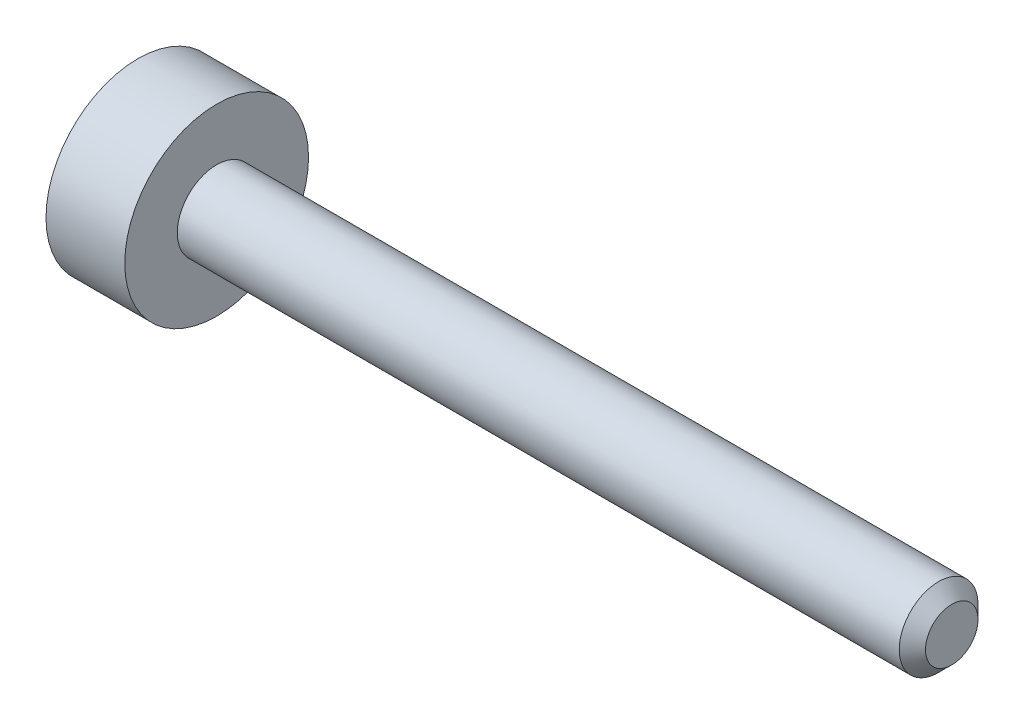
SolidWorks part; units mm, degrees
material "AISI 1020"
ref_plane "Front Plane" through (0, 0, 0) normal (0, 0, 1) x (1, 0, 0)
ref_plane "Top Plane" through (0, 0, 0) normal (0, 1, 0) x (1, 0, 0)
ref_plane "Right Plane" through (0, 0, 0) normal (1, 0, 0) x (0, 0, -1)
sketch "Sketch1" plane through (0, 0, 0) normal (0, 0, 1) x (1, 0, 0)
  line L0 (0, 0) -> (4.55, 0) construction
  line L1 (0, 0) -> (0, 1)
  line L2 (0, 1) -> (-0.5, 1.5)
  line L3 (-0.5, 1.5) -> (-28, 1.5)
  line L4 (-28, 1.5) -> (-28, 3.5)
  line L5 (-28, 3.5) -> (-31, 3.5)
  line L6 (-31, 3.5) -> (-31, 0)
  line L7 (-31, 0) -> (0, 0)
  dimension "D1" = 3
  dimension "D2" = 7
  dimension "D3" = 3
  dimension "D4" = 28
  dimension "D5" = 0.5
  dimension "D6" = 0.5
revolve "Revolve1" add sketch "Sketch1" angle 360 about L0
sketch "Sketch2" plane through (-31, 0, 0) normal (-1, 0, 0) x (0, 0, 1)
  line L1 (0, 1.7321) -> (-1.5, 0.866)
  line L2 (-1.5, 0.866) -> (-1.5, -0.866)
  line L3 (-1.5, -0.866) -> (0, -1.7321)
  line L4 (0, -1.7321) -> (1.5, -0.866)
  line L5 (1.5, -0.866) -> (1.5, 0.866)
  line L6 (1.5, 0.866) -> (0, 1.7321)
  circle A0 centre (0, 0) radius 1.5 construction
  dimension "D1" = 3
extrude "Cut-Extrude1" cut sketch "Sketch2" against normal blind 1.5
